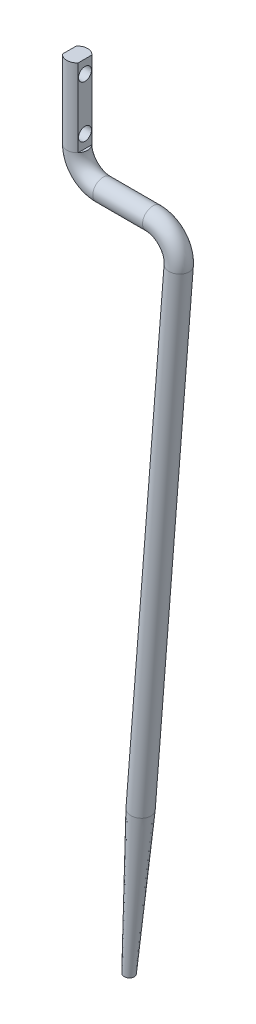
SolidWorks part; units mm, degrees
material "AISI 304"
ref_plane "前视基准面" through (0, 0, 0) normal (0, 0, 1) x (1, 0, 0)
ref_plane "上视基准面" through (0, 0, 0) normal (0, 1, 0) x (1, 0, 0)
ref_plane "右视基准面" through (0, 0, 0) normal (1, 0, 0) x (0, 0, -1)
sketch "Sketch1" plane through (0, 0, 0) normal (0, 0, 1) x (1, 0, 0)
  line L0 (0, 40) -> (0, 10)
  line L1 (10, 0) -> (29.1916, 0)
  line L2 (39.1614, -10.7759) -> (20, -257)
  arc A0 (29.1916, 0) -> (39.1614, -10.7759) centre (29.1916, -10) cw
  arc A1 (0, 10) -> (10, 0) centre (10, 10) ccw
  point P7 (40, 0)
  point P10 (0, 0)
  dimension "D5" = 10
  dimension "D1" = 40
  dimension "D2" = 40
  dimension "D3" = 257
  dimension "D4" = 20
ref_plane "Plane1" through (0, 40, 0) normal (0, 1, 0) x (1, 0, 0)
sketch "Sketch3" plane through (0, 40, 0) normal (0, 1, 0) x (1, 0, 0)
  circle A0 centre (0, 0) radius 4
  dimension "D1" = 8
sweep "Sweep1" add profiles "Sketch3" path "Sketch1"
chamfer "Chamfer1" distance 2 angle 88 1 edges at (20, -257, 4)
sketch "Sketch4" plane through (0, 40, 0) normal (0, 1, 0) x (1, 0, 0)
  line L1 (3, 17.7651) -> (-3, 17.7651)
  line L2 (3, 17.7651) -> (3, -17.7651)
  line L3 (3, -17.7651) -> (-3, -17.7651)
  line L4 (-3, 17.7651) -> (-3, -17.7651)
  line L5 (3, 17.7651) -> (-3, -17.7651) construction
  line L6 (3, -17.7651) -> (-3, 17.7651) construction
  point P0 (0, 0)
  dimension "D1" = 3
extrude "Extrude1" cut sketch "Sketch4" against normal blind 30 flip side to cut
hole_wizard "M6 Tapped Hole1" positions "Sketch5" profile "Sketch6" tap size "M6" standard "GB"
sketch "Sketch5" plane through (3, 0, 0) normal (1, 0, 0) x (0, 0, -1)
  line L0 (-2.6458, 10) -> (2.6458, 10) construction
  point P0 (0, 35)
  point P2 (0, 15)
  dimension "D1" = 20
  dimension "D2" = 5
sketch "Sketch6" plane through (3, 35, 0) normal (0, 1, 0) x (0, 0, -1)
  line L0 (0, 0) -> (0, 10.5022)
  line L1 (0, 10.5022) -> (2.5, 9)
  line L2 (2.5, 9) -> (2.5, 0)
  line L5 (2.5, 0) -> (0, 0)
  line L10 (0, 10.5022) -> (-2.5, 9) construction
  line L11 (0, -6.35) -> (0, 107.95) construction
  dimension "螺纹孔钻头直径" = 5
  dimension "螺纹孔钻头深度" = 9
  dimension "导头角度" = 118
